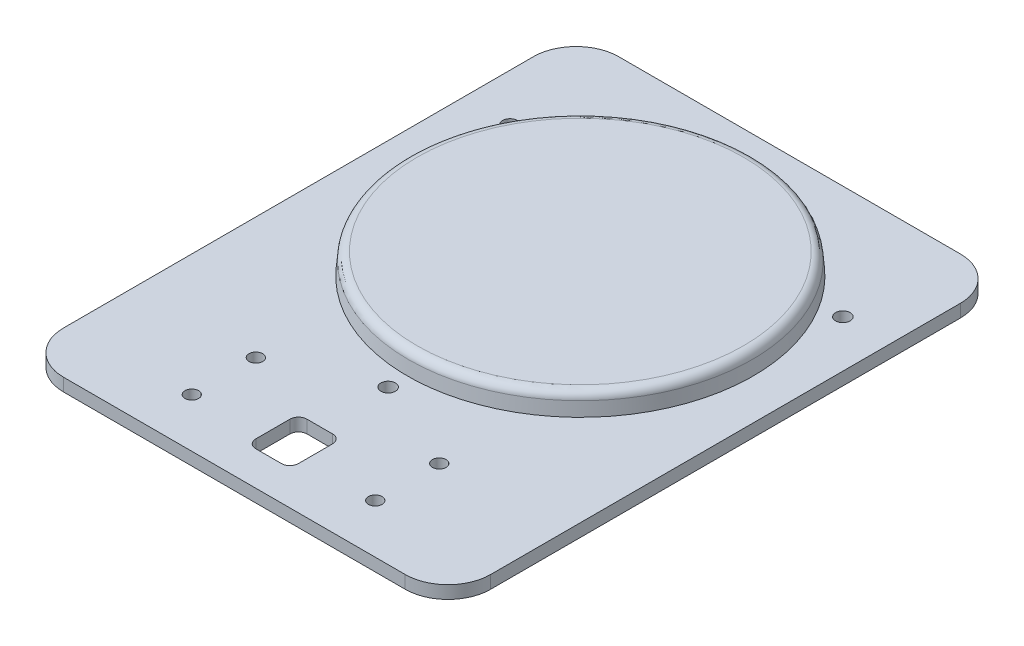
SolidWorks part; units mm, degrees
ref_plane "Front" through (0, 0, 0) normal (0, 0, 1) x (1, 0, 0)
ref_plane "Top" through (0, 0, 0) normal (0, 1, 0) x (1, 0, 0)
ref_plane "Right" through (0, 0, 0) normal (1, 0, 0) x (0, 0, -1)
sketch "Sketch1" plane through (0, 0, 0) normal (0, 1, 0) x (1, 0, 0)
  line L0 (0, 65) -> (0, -65) construction
  line L1 (0, 65) -> (0, -65) construction
  line L3 (40, -65) -> (-40, -65)
  line L4 (50, -55) -> (50, 55)
  line L5 (40, 65) -> (-40, 65)
  line L6 (-50, -55) -> (-50, 55)
  line L7 (50, -65) -> (-50, 65) construction
  line L8 (50, 65) -> (-50, -65) construction
  line L9 (3, -57) -> (-3, -57)
  line L10 (5, -55) -> (5, -47)
  line L11 (3, -45) -> (-3, -45)
  line L12 (-5, -55) -> (-5, -47)
  line L13 (5, -57) -> (-5, -45) construction
  line L14 (5, -45) -> (-5, -57) construction
  arc A0 (-50, 55) -> (-40, 65) centre (-40, 55) cw
  arc A1 (40, 65) -> (50, 55) centre (40, 55) cw
  arc A2 (50, -55) -> (40, -65) centre (40, -55) cw
  arc A3 (-40, -65) -> (-50, -55) centre (-40, -55) cw
  circle A4 centre (21.475, -38.5) radius 1.6 construction
  circle A5 centre (21.475, -53.5) radius 1.6 construction
  circle A6 centre (-21.475, -38.5) radius 1.6 construction
  circle A7 centre (-21.475, -53.5) radius 1.6 construction
  circle A8 centre (21.475, -38.5) radius 1.6
  circle A9 centre (21.475, -53.5) radius 1.6
  circle A10 centre (-21.475, -38.5) radius 1.6
  circle A11 centre (-21.475, -53.5) radius 1.6
  circle A12 centre (0, 16) radius 42.5 construction
  circle A13 centre (0, 16) radius 42.5 construction
  circle A14 centre (0, -29) radius 1.7
  circle A15 centre (-38.9711, 38.5) radius 1.7
  circle A16 centre (38.9711, 38.5) radius 1.7
  arc A17 (3, -57) -> (5, -55) centre (3, -55) ccw
  arc A18 (5, -47) -> (3, -45) centre (3, -47) ccw
  arc A19 (-3, -45) -> (-5, -47) centre (-3, -47) ccw
  arc A20 (-5, -55) -> (-3, -57) centre (-3, -55) ccw
  point P2 (0, 0)
  point P8 (0, -51)
  point P44 (0, 16)
  dimension "D2" = 10
  dimension "D3" = 3.4
  dimension "D9" = 2
  dimension "D1" = 100
  dimension "D4" = 45
  dimension "D6" = 12
  dimension "D7" = 10
  dimension "D8" = 8
  dimension "D5" = 3
extrude "Boss-Extrude1" add sketch "Sketch1" against normal blind 3
sketch "Sketch2" plane through (0, 0, 0) normal (0, 1, 0) x (1, 0, 0)
  circle A2 centre (0, 16) radius 40.5
  circle A3 centre (0, 16) radius 40.5
  dimension "D1" = 1
extrude "Boss-Extrude2" add sketch "Sketch2" along normal blind 5 draft 5
fillet "Fillet1" radius 2 1 edges at (0, 5, 24.0626)
